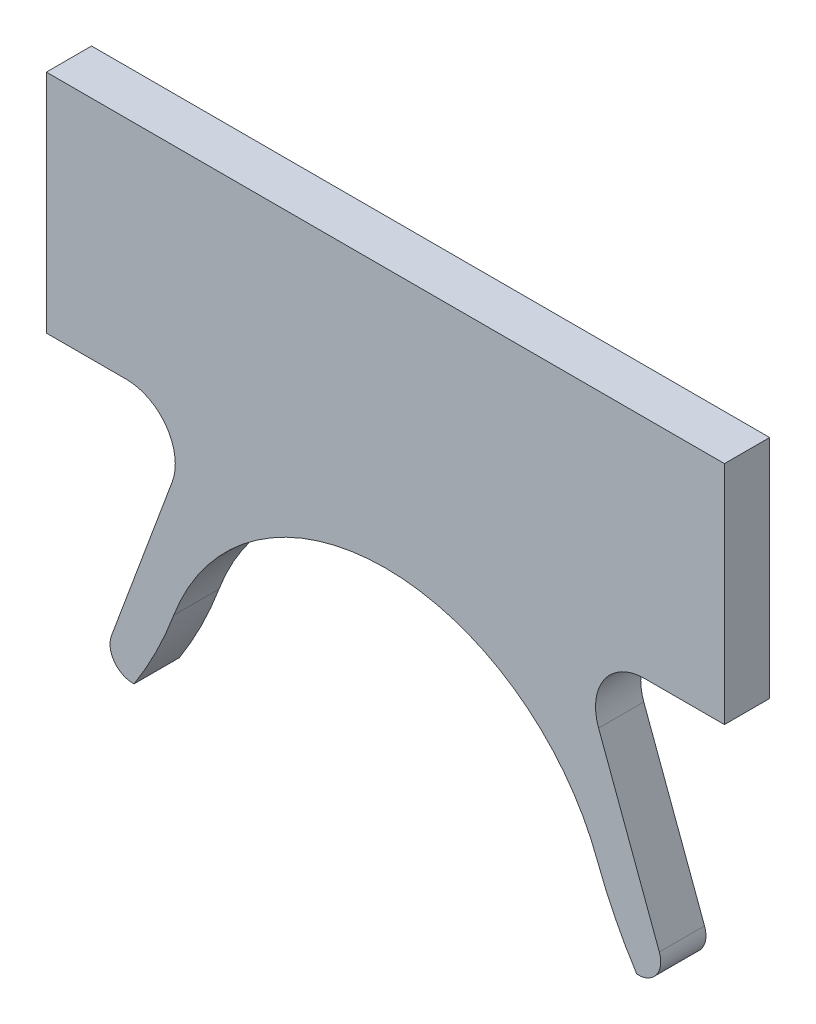
SolidWorks part; units mm, degrees
ref_plane "前视基准面" through (0, 0, 0) normal (0, 0, 1) x (1, 0, 0)
ref_plane "上视基准面" through (0, 0, 0) normal (0, 1, 0) x (1, 0, 0)
ref_plane "右视基准面" through (0, 0, 0) normal (1, 0, 0) x (0, 0, -1)
sketch "草图1" plane through (0, 0, 0) normal (0, 0, 1) x (1, 0, 0)
  line L0 (-40.1301, 0) -> (40.2192, 0) construction
  line L1 (0, 0) -> (0, 40.7888) construction
  line L2 (-22.2394, 0) -> (-22.3629, 0)
  line L3 (22.2394, 0) -> (22.3629, 0)
  line L4 (-30, 23) -> (-30, 43)
  line L5 (-30, 43) -> (30, 43)
  line L6 (30, 43) -> (30, 23)
  line L7 (-24.2377, 2.6964) -> (-18.8627, 17.1663)
  line L9 (24.2377, 2.6964) -> (18.8627, 17.1663)
  line L10 (-30, 23) -> (-22.9189, 23)
  line L11 (22.9189, 23) -> (30, 23)
  arc A0 (18.7312, 7.0101) -> (-18.7312, 7.0101) centre (0, 0) ccw
  arc A1 (-22.2394, 0) -> (-18.7312, 7.0101) centre (-53.4627, 20.0083) ccw
  arc A2 (22.2394, 0) -> (18.7312, 7.0101) centre (53.4627, 20.0083) cw
  arc A3 (-18.8627, 17.1663) -> (-22.9189, 23) centre (-22.9189, 18.673) ccw
  arc A4 (18.8627, 17.1663) -> (22.9189, 23) centre (22.9189, 18.673) cw
  arc A5 (-24.2377, 2.6964) -> (-22.3629, 0) centre (-22.3629, 2) ccw
  arc A6 (24.2377, 2.6964) -> (22.3629, 0) centre (22.3629, 2) cw
  point P20 (0, 23)
  point P26 (-25.2394, 0)
  point P29 (25.2394, 0)
  dimension "D1" = 40
  dimension "D3" = 37.0841
  dimension "D4" = 2
  dimension "D6" = 2
  dimension "D2" = 20
  dimension "D5" = 3
extrude "凸台-拉伸1" add sketch "草图1" along normal blind 4
